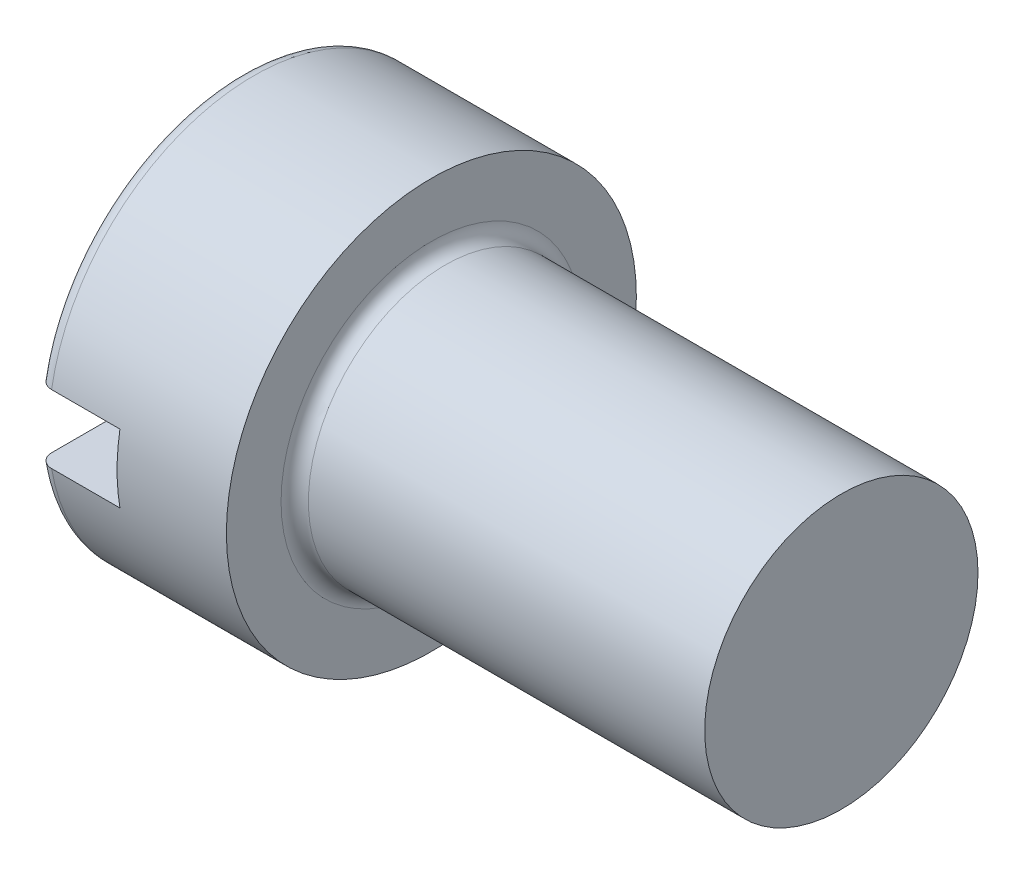
SolidWorks part; units mm, degrees
ref_plane "Front" through (0, 0, 0) normal (0, 0, 1) x (1, 0, 0)
ref_plane "Top" through (0, 0, 0) normal (0, 1, 0) x (1, 0, 0)
ref_plane "Right" through (0, 0, 0) normal (1, 0, 0) x (0, 0, -1)
other "Configuration Table"
ref_plane "Plane1" through (1.4, 0, 0) normal (1, 0, 0) x (0, 0, -1)
sketch "Sketch2" plane through (1.4, 0, 0) normal (1, 0, 0) x (0, 0, -1)
  circle A0 centre (0, 0) radius 1.9
  dimension "dk" = 3.8
extrude "BaseHead" add sketch "Sketch2" against normal blind 1.4 draft 3
sketch "Sketch3" plane through (1.4, -1.1101, -1.3544) normal (1, 0, 0) x (0, 0, -1)
  line L0 (-1.3544, 1.1101) -> (-0.5544, 1.1101) construction
  circle A0 centre (-1.3544, 1.1101) radius 1
  circle A1 centre (-1.3544, 1.1101) radius 1.9 construction
  dimension "d" = 2
  dimension "a" = 0.8
extrude "BaseBody" add sketch "Sketch3" along normal blind 3
cosmetic thread "ThreadCosmetic1" [suppressed] parameters "D1"=3, "D2"=1.567
sketch "Sketch4" plane through (-1.9, -1.9, 0) normal (0, 0, 1) x (0, 1, 0)
  line L1 (1.65, -1.9) -> (2.15, -1.9)
  line L2 (1.65, -1.9) -> (1.65, -2.5)
  line L3 (1.65, -2.5) -> (2.15, -2.5)
  line L4 (2.15, -1.9) -> (2.15, -2.5)
  line L5 (3.7266, -1.9) -> (0.0734, -1.9) construction
  dimension "n" = 0.5
  dimension "t" = 0.6
  dimension "m" = 0.25
extrude "Slot" cut sketch "Sketch4" against normal through all and the other way through all
fillet "HeadFillet" radius 0.1 3 edges at (1.4, 0, -1) (0, -1.8266, 0) (0, 1.8266, 0)
sketch "Sketch1" plane through (0, 0, 0) normal (0, 0, 1) x (1, 0, 0)
  line L0 (5.5483, 0) -> (-2.9147, 0) construction
  line L1 (1.4, 5.7835) -> (-20.6, 5.7835)
  line L2 (1.4, 5.7835) -> (1.4, 0.7835)
  line L3 (1.4, 0.7835) -> (-21.6, 0.7835)
  line L8 (-20.6, 1) -> (-21.6, 0.7835)
  line L9 (-20.6, 5.7835) -> (-20.6, 1)
  line L10 (1.4, -1.9) -> (1.4, 1.9) construction
  line L11 (4.4, -1) -> (4.4, 1) construction
  line L12 (4.4, 1) -> (1.5, 1) construction
  dimension "b1" = 1.567
  dimension "b" = 25
  dimension "x" = 1
  dimension "dd" = 5
sketch "Sketch5" plane through (0, 0, 0) normal (0, 0, 1) x (1, 0, 0)
  line L0 (4.5082, 1) -> (4.5082, 1.2165)
  line L1 (4.5082, 1.2165) -> (4.2917, 1.2165)
  line L2 (4.2917, 1.2165) -> (4.2917, 1)
  line L3 (4.2917, 1) -> (4.4, 0.8125)
  line L4 (4.4, 0.8125) -> (4.5082, 1)
  line L5 (4.4, -1) -> (4.4, 1) construction
  line L6 (0, 0) -> (15.9087, 0) construction
  dimension "D1" = 2
  dimension "D2" = 0.2165
revolve "Cut-Revolve10" [suppressed] cut sketch "Sketch5" angle 360 about L6
pattern_linear "LPattern10" [suppressed] count 12 spacing 0.2598 along (1, 0, 0)
sketch "草图1" plane through (0, 0, 0) normal (-1, 0, 0) x (0, 0, 1)
  circle A0 centre (0, 0) radius 1.5
  dimension "D1" = 3
extrude "切除-拉伸1" cut sketch "草图1" against normal through all flip side to cut
fillet "圆角1" radius 0.1 2 edges at (0, -1.5, 0) (0, 1.5, 0)
equation "\"m@Sketch4\" = \"n@Sketch4\" / 2"
equation "\"D1@Plane1\"=\"k@BaseHead\""
equation "\"D1@Sketch5\" = \"d@Sketch3\""
equation "\"D2@Sketch5\" =  ( \"d@Sketch3\" - \"D2@ThreadCosmetic1\" )  / 2"
equation "\"D3@LPattern10\" = \"D2@Sketch5\" * 1.2"
equation "\"D1@LPattern10\" = \"D1@ThreadCosmetic1\" / \"D3@LPattern10\""
